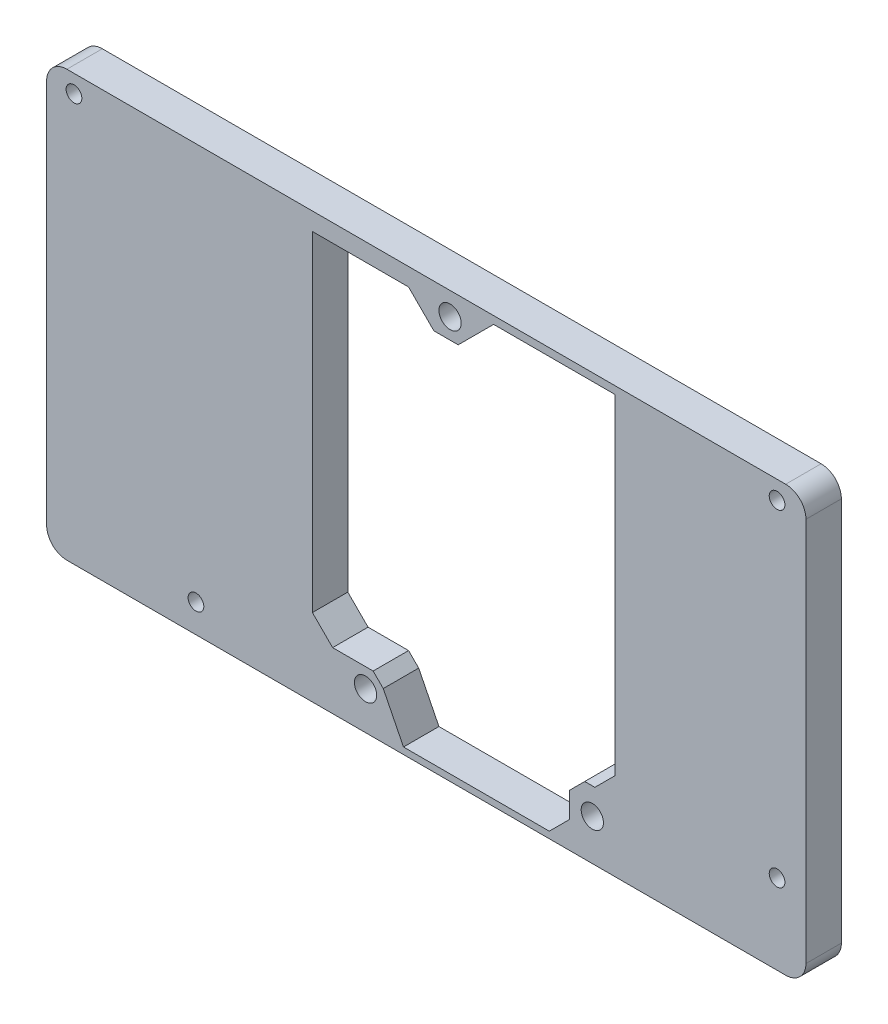
SolidWorks part; units mm, degrees
material "Plastique personnalisé"
ref_plane "Plan de face" through (0, 0, 0) normal (0, 0, 1) x (1, 0, 0)
ref_plane "Plan de dessus" through (0, 0, 0) normal (0, 1, 0) x (1, 0, 0)
ref_plane "Plan de droite" through (0, 0, 0) normal (1, 0, 0) x (0, 0, -1)
sketch "Esquisse1" plane through (-8.4, 23.4, 0) normal (0, 0, 1) x (0, -1, 0)
  line L0 (36.1, 41.8) -> (32.1, 45.8)
  line L1 (-33.1, 45.8) -> (32.1, 45.8)
  line L2 (-33.1, 45.8) -> (-33.1, 21.8)
  line L5 (36.1, 41.8) -> (36.1, 39.8)
  line L6 (36.1, 39.8) -> (39.1, 36.8)
  line L7 (39.1, 36.8) -> (44.1, 36.8)
  line L8 (48.1, 32.8) -> (44.1, 36.8)
  line L9 (38.1, -10) -> (34.1, -14)
  line L10 (38.1, -10) -> (38.1, -2)
  line L11 (38.1, -2) -> (40.1, 0)
  line L12 (40.1, 0) -> (48.1, 4)
  line L13 (48.1, 4) -> (48.1, 32.8)
  line L14 (34.1, -14) -> (-31.1, -14)
  line L15 (-31.1, -14) -> (-31.1, 5)
  line L16 (-31.1, 5) -> (-26.1, 10)
  line L17 (-26.1, 10) -> (-26.1, 14.8)
  line L18 (-26.1, 14.8) -> (-33.1, 21.8)
  circle A0 centre (-30.1, 13.2) radius 2.2
  circle A1 centre (41.3, 41.3) radius 2.2
  circle A2 centre (41.9, -3.5) radius 2.2
sketch "Esquisse2" plane through (0, 0, 0) normal (0, 0, 1) x (1, 0, 0)
  line L0 (0.1, 60) -> (-87.6667, 60) construction
  line L2 (-74.9, 17) -> (-74.9, 68.6807) construction
  line L4 (0.1, -26) -> (91.1062, -26) construction
  line L6 (75.1, 17) -> (75.1, -34.1533) construction
  line L9 (-74.9, 60) -> (75.1, 60)
  line L10 (-74.9, 60) -> (-74.9, -26)
  line L11 (-74.9, -26) -> (75.1, -26)
  line L12 (75.1, 60) -> (75.1, -26)
  circle A0 centre (-69.5, 54.5) radius 1.55
  circle A1 centre (69.4, 54.4) radius 1.55
  circle A2 centre (69.4, -10.2) radius 1.55
  circle A3 centre (-45.4, -20.4) radius 1.55
extrude "Boss.-Extru.1" add sketch "Esquisse2" along normal blind 7
extrude "Enlèv. mat.-Extru.1" cut sketch "Esquisse1" against normal through all and the other way through all
sketch "Esquisse3" plane through (0, 0, 0) normal (0, 0, 1) x (1, 0, 0)
  line L0 (-74.9, 60) -> (-74.9, 58.0069) construction
  line L2 (-74.9, 58.0069) -> (75.1, 58.0069) construction
  line L5 (-74.9, 58.0069) -> (91.3074, 58.0069)
  line L6 (-74.9, 58.0069) -> (-74.9, 123.7094)
  line L7 (-74.9, 123.7094) -> (91.3074, 123.7094)
  line L8 (91.3074, 58.0069) -> (91.3074, 123.7094)
extrude "Enlèv. mat.-Extru.2" cut sketch "Esquisse3" along normal through all
fillet "Congé1" radius 4 4 edges at (75.1, -26, 3.5) (-74.9, -26, 3.5) (75.1, 58.0069, 3.5) (-74.9, 58.0069, 3.5)
